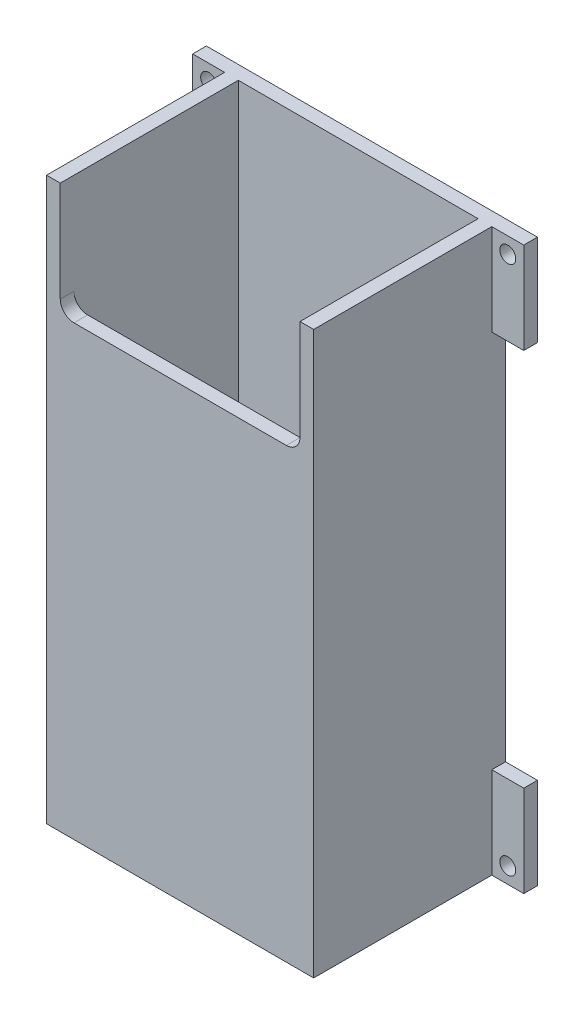
SolidWorks part; units mm, degrees
material "黄铜"
ref_plane "前视基准面" through (0, 0, 0) normal (0, 0, 1) x (1, 0, 0)
ref_plane "上视基准面" through (0, 0, 0) normal (0, 1, 0) x (1, 0, 0)
ref_plane "右视基准面" through (0, 0, 0) normal (1, 0, 0) x (0, 0, -1)
sketch "草图1" plane through (0, 0, 0) normal (0, 1, 0) x (1, 0, 0)
  line L1 (0, 0) -> (58.5, 0)
  line L2 (0, 0) -> (0, 42)
  line L3 (0, 42) -> (58.5, 42)
  line L4 (58.5, 0) -> (58.5, 42)
  dimension "D1" = 42
  dimension "D2" = 58.5
extrude "凸台-拉伸1" add sketch "草图1" along normal blind 123
sketch "草图2" plane through (0, 123, 0) normal (0, 1, 0) x (1, 0, 0)
  line L0 (0, 0) -> (58.5, 42)
  line L2 (3, 3) -> (55.5, 3)
  line L3 (3, 3) -> (3, 39)
  line L4 (3, 39) -> (55.5, 39)
  line L5 (55.5, 3) -> (55.5, 39)
  line L6 (3, 3) -> (55.5, 39) construction
  line L7 (3, 39) -> (55.5, 3) construction
  point P4 (29.25, 21)
  dimension "D1" = 36
  dimension "D2" = 52.5
extrude "切除-拉伸1" cut sketch "草图2" against normal blind 120 contours L4 L3 L2 L0 | L2 L5 L4 L0
sketch "草图3" plane through (0, 123, 0) normal (0, 1, 0) x (1, 0, 0)
  line L0 (0, 0) -> (58.5, 0) construction
  line L1 (3, 3) -> (55.5, 3)
  line L2 (3, 3) -> (3, 0)
  line L3 (3, 0) -> (55.5, 0)
  line L4 (55.5, 3) -> (55.5, 0)
  dimension "D1" = 52.5
extrude "切除-拉伸2" cut sketch "草图3" against normal blind 25
fillet "圆角1" radius 3 2 edges at (55.5, 98, -1.5) (3, 98, -1.5)
sketch "草图4" plane through (0, 0, -42) normal (0, 0, -1) x (-1, 0, 0)
  line L0 (-58.5, 123) -> (0, 0)
  line L1 (0, 123) -> (0, 0) construction
  line L2 (-65.5, 123) -> (7, 123)
  line L3 (-65.5, 123) -> (-65.5, 0)
  line L4 (-65.5, 0) -> (7, 0)
  line L5 (7, 123) -> (7, 0)
  line L6 (-65.5, 123) -> (7, 0) construction
  line L7 (-65.5, 0) -> (7, 123) construction
  line L8 (-58.5, 123) -> (-58.5, 0)
  line L9 (0, 123) -> (0, 0)
  point P4 (-29.25, 61.5)
  line M6 (0, 0) -> (0, 123)
  line M8 (-58.5, 123) -> (-58.5, 0)
  dimension "D1" = 123
  dimension "D2" = 7
extrude "凸台-拉伸2" add sketch "草图4" against normal blind 3 contours L3 L4 L2 M8 | L5 L2 L4 M6
sketch "草图5" plane through (0, 0, -42) normal (0, 0, -1) x (-1, 0, 0)
  line L0 (-65.5, 123) -> (7, 123) construction
  line L1 (-65.5, 123) -> (-65.5, 0) construction
  line L2 (7, 123) -> (7, 0) construction
  line L3 (-65.5, 0) -> (7, 0) construction
  point P0 (-62, 119.5)
  point P1 (3.5, 119.5)
  point P2 (-62, 3.5)
  point P3 (3.5, 3.5)
  dimension "D1" = 3.5
  dimension "D2" = 3.5
  dimension "D3" = 3.5
  dimension "D4" = 3.5
  dimension "D5" = 3.5
  dimension "D6" = 3.5
  dimension "D7" = 3.5
  dimension "D8" = 3.5
sketch "草图6" plane through (0, 0, -42) normal (0, 0, -1) x (-1, 0, 0)
  point P0 (-62, 3.5)
  point P3 (3.5, 3.5)
  point P6 (3.5, 119.5)
  point P9 (-62, 119.5)
hole_wizard "孔1" positions "草图6" profile "草图7" legacy end condition through all
sketch "草图7" plane through (62, 3.5, -42) normal (1, 0, 0) x (0, 1, 0)
  line L0 (0, 0) -> (0, 42)
  line L1 (0, 42) -> (1.75, 42)
  line L2 (1.75, 42) -> (1.75, 0)
  line L3 (1.75, 0) -> (0, 0)
  line L4 (0, 110) -> (0, -10) construction
  dimension "直径" = 3.5
  dimension "深度" = 42
sketch "草图7" plane through (0, 0, -42) normal (0, 0, -1) x (-1, 0, 0)
  line L0 (7, 123) -> (7, 0) construction
  line L1 (7, 103) -> (0, 103)
  line L2 (7, 103) -> (7, 20)
  line L3 (7, 20) -> (0, 20)
  line L4 (0, 103) -> (0, 20)
  line L5 (-65.5, 0) -> (7, 0) construction
  line L6 (-65.5, 123) -> (-65.5, 0) construction
  line L7 (-65.5, 103) -> (-58.5, 103)
  line L8 (-65.5, 103) -> (-65.5, 20)
  line L9 (-65.5, 20) -> (-58.5, 20)
  line L10 (-58.5, 103) -> (-58.5, 20)
  line L11 (-65.5, 123) -> (7, 123) construction
  dimension "D1" = 20
  dimension "D2" = 20
  dimension "D3" = 7
  dimension "D4" = 20
  dimension "D5" = 20
  dimension "D6" = 7
extrude "切除-拉伸3" cut sketch "草图7" against normal blind 3 contours L8 L7 L10 L9 | L2 L1 L4 L3
sketch "草图8" plane through (0, 0, 0) normal (0, 0, 1) x (1, 0, 0)
  line L0 (58.5, 123) -> (58.5, 0) construction
  line L1 (58.5, 70) -> (55.5, 70)
  line L2 (58.5, 70) -> (58.5, 81.5)
  line L3 (58.5, 81.5) -> (55.5, 81.5)
  line L4 (55.5, 70) -> (55.5, 81.5)
  line L5 (0, 0) -> (58.5, 0) construction
  line L7 (58.5, 70) -> (55.5, 70)
  line L8 (58.5, 70) -> (58.5, 58.5)
  line L9 (58.5, 58.5) -> (55.5, 58.5)
  line L10 (55.5, 70) -> (55.5, 58.5)
  dimension "D1" = 70
  dimension "D2" = 11.5
  dimension "D3" = 11.5
  dimension "D4" = 3
  dimension "D5" = 3
sketch "草图9" plane through (0, 3, 0) normal (0, 1, 0) x (1, 0, 0)
  line L1 (3, 39) -> (55.5, 39)
  line L2 (3, 39) -> (3, 3)
  line L3 (3, 3) -> (55.5, 3)
  line L4 (55.5, 39) -> (55.5, 3)
extrude "凸台-拉伸3" add sketch "草图9" along normal blind 10
